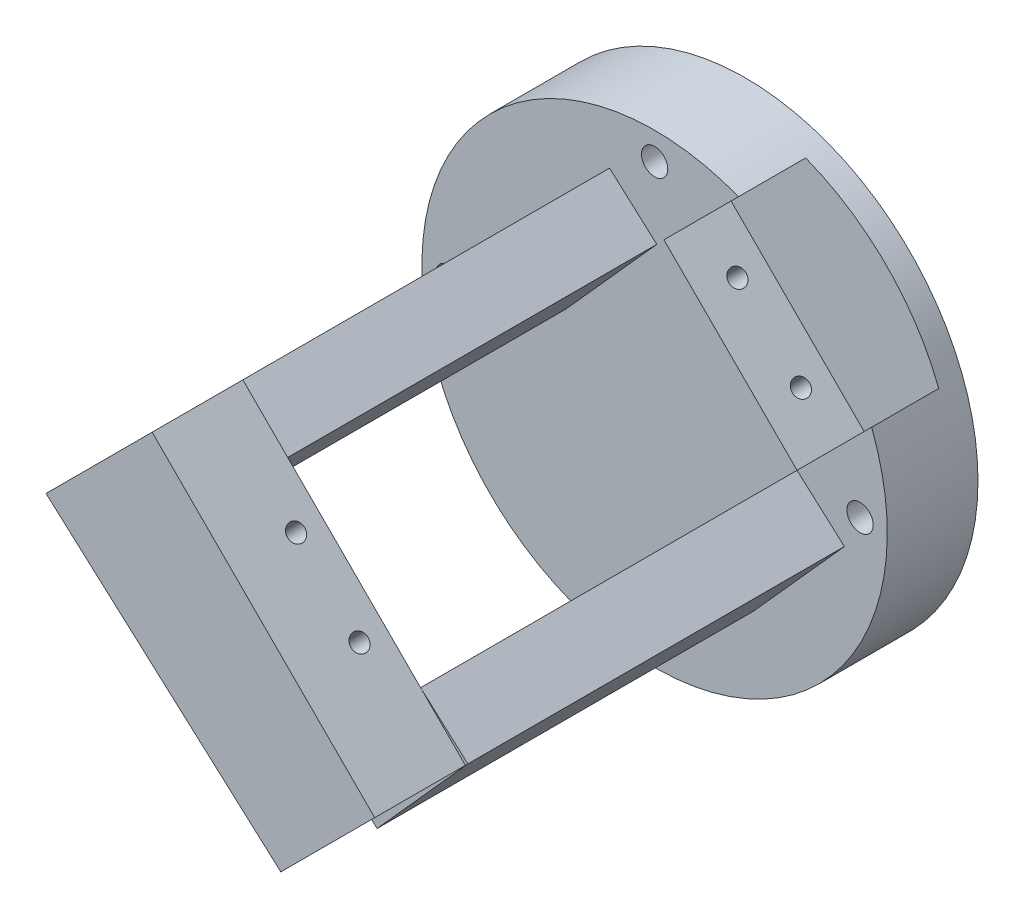
SolidWorks part; units mm, degrees
ref_plane "Front Plane" through (0, 0, 0) normal (0, 0, 1) x (1, 0, 0)
ref_plane "Top Plane" through (0, 0, 0) normal (0, 1, 0) x (1, 0, 0)
ref_plane "Right Plane" through (0, 0, 0) normal (1, 0, 0) x (0, 0, -1)
sketch "Sketch1" plane through (0, 0, 0) normal (0, 0, 1) x (1, 0, 0)
  circle A0 centre (0, 0) radius 25.65
  circle A2 centre (0, -22.65) radius 1.45
  circle A3 centre (0, -22.65) radius 1.45
  circle A4 centre (22.65, 0) radius 1.45
  circle A5 centre (22.65, 0) radius 1.45
  circle A6 centre (0, 22.65) radius 1.45
  circle A7 centre (0, 22.65) radius 1.45
  circle A8 centre (-22.65, 0) radius 1.45
  circle A9 centre (-22.65, 0) radius 1.45
  dimension "D1" = 0
  dimension "D2" = 0
  dimension "D3" = 0
  dimension "D4" = 0
extrude "Boss-Extrude1" add sketch "Sketch1" along normal blind 10 contours A0
sketch "Sketch2" plane through (0, 0, 10) normal (0, 0, 1) x (1, 0, 0)
  line L0 (0, 0) -> (18.1373, 18.1373) construction
  line L1 (1.0288, 15.7013) -> (15.7013, 1.0288)
  line L2 (15.7013, 1.0288) -> (19.2002, 4.5278) construction
  line L8 (10.6985, 10.6985) -> (11.2642, 10.1328) construction
  line L9 (10.1328, 11.2642) -> (11.2642, 10.1328) construction
  line L13 (1.0288, 15.7013) -> (9.2511, 23.9236)
  line L14 (15.7013, 1.0288) -> (23.9236, 9.2511)
  circle A0 centre (0, 0) radius 25.65 construction
  point P5 (10.6985, 10.6985)
  point P6 (8.3651, 8.3651)
  point P13 (10.6985, 10.6985)
  point P14 (8.3651, 8.3651)
  point P19 (12.3249, 12.3249)
  dimension "D1" = 10.52
  dimension "D2" = 3.3
  dimension "D3" = 20.75
extrude "Cut-Extrude2" cut sketch "Sketch2" against normal blind 7.4 and the other way through all
sketch "Sketch3" plane through (8.3651, 8.3651, 0) normal (0.7071, 0.7071, 0) x (0, 0, -1)
  line L0 (-10, 0) -> (-2.6, 0) construction
  line L1 (-10, 10.375) -> (-10, -10.375) construction
  line L2 (-2.6, 10.375) -> (-2.6, -10.375) construction
  circle A0 centre (-5.74, 4.95) radius 2.25 construction
  circle A1 centre (-5.74, 4.95) radius 0.95
  circle A2 centre (-5.74, -4.95) radius 0.95
  dimension "D1" = 2.7
  dimension "D2" = 4.5
  dimension "D3" = 2.01
  dimension "D4" = 1.9
extrude "Cut-Extrude3" cut sketch "Sketch3" against normal blind 10
sketch "Sketch5" plane through (0, 0, 10) normal (0, 0, 1) x (1, 0, 0)
  line L0 (15.7013, 1.0288) -> (5.6932, -10.1442)
  line L1 (7.9733, 7.9511) -> (-2.728, -3.9958) construction
  line L2 (20.9154, -3.6416) -> (10.9073, -14.8147)
  line L3 (15.7013, 1.0288) -> (20.9154, -3.6416)
  line L4 (5.6932, -10.1442) -> (10.9073, -14.8147)
  line L5 (0.2452, 14.8734) -> (-4.9689, 19.5438)
  line L6 (-4.9689, 19.5438) -> (-14.977, 8.3708)
  line L7 (-9.7629, 3.7003) -> (-14.977, 8.3708)
  line L8 (0.2452, 14.8734) -> (-9.7629, 3.7003)
  line L9 (15.7013, 1.0288) -> (5.6932, -10.1442) construction
  point P6 (0, 0)
  dimension "D1" = 15
  dimension "D2" = 7
extrude "Boss-Extrude2" add sketch "Sketch5" along normal blind 41.5
sketch "Sketch7" plane through (8.3651, 8.3651, 0) normal (0.7071, 0.7071, 0) x (0, 0, -1)
  line L0 (-30.75, -10.375) -> (-30.75, 10.3437) construction
  line L1 (-51.5, -10.375) -> (-10, -10.375) construction
  line L2 (-51.5, 10.3437) -> (-10, 10.3437) construction
  line L3 (-51.5, 17.3331) -> (-10, 17.3331) construction
  line L4 (-51.5, -17.3644) -> (-61.5, -17.3644)
  line L5 (-51.5, -17.3644) -> (-51.5, 17.3331)
  line L6 (-51.5, 17.3331) -> (-61.5, 17.3331)
  line L7 (-61.5, -17.3644) -> (-61.5, 17.3331)
  circle A0 centre (-5.74, -4.95) radius 0.95 construction
  circle A1 centre (-5.74, 4.95) radius 0.95 construction
  circle A2 centre (-5.74, -4.95) radius 0.95
  circle A3 centre (-5.74, 4.95) radius 0.95
  circle A4 centre (-54.39, -4.95) radius 0.95
  circle A5 centre (-54.39, 4.95) radius 0.95
  point P23 (0, 0)
  dimension "D1" = 10
extrude "Boss-Extrude3" add sketch "Sketch7" against normal up to surface (14.6383 mm away) contours L5 L4 L7 L6
sketch "Sketch11" plane through (8.3651, 8.3651, 0) normal (0.7071, 0.7071, 0) x (0, 0, -1)
  line L4 (-2.6, 10.375) -> (-10, 10.375)
  line L5 (-10, 10.375) -> (-10, -10.375)
  line L6 (-10, -10.375) -> (-2.6, -10.375)
  line L7 (-2.6, -10.375) -> (-2.6, 10.375)
  line L8 (-2.6, 10.375) -> (-10, 10.375)
  line L9 (-10, 10.375) -> (-10, -10.375)
  line L10 (-10, -10.375) -> (-2.6, -10.375)
  line L11 (-2.6, -10.375) -> (-2.6, 10.375)
  circle A1 centre (-5.74, -4.95) radius 0.95
  circle A2 centre (-5.74, -4.95) radius 0.95
  circle A3 centre (-5.74, 4.95) radius 0.95
  circle A4 centre (-5.74, 4.95) radius 0.95
  dimension "D1" = 0
  dimension "D2" = 0
  dimension "D3" = 0
extrude "Cut-Extrude4" cut sketch "Sketch11" against normal blind 15 contours A2 | A4
